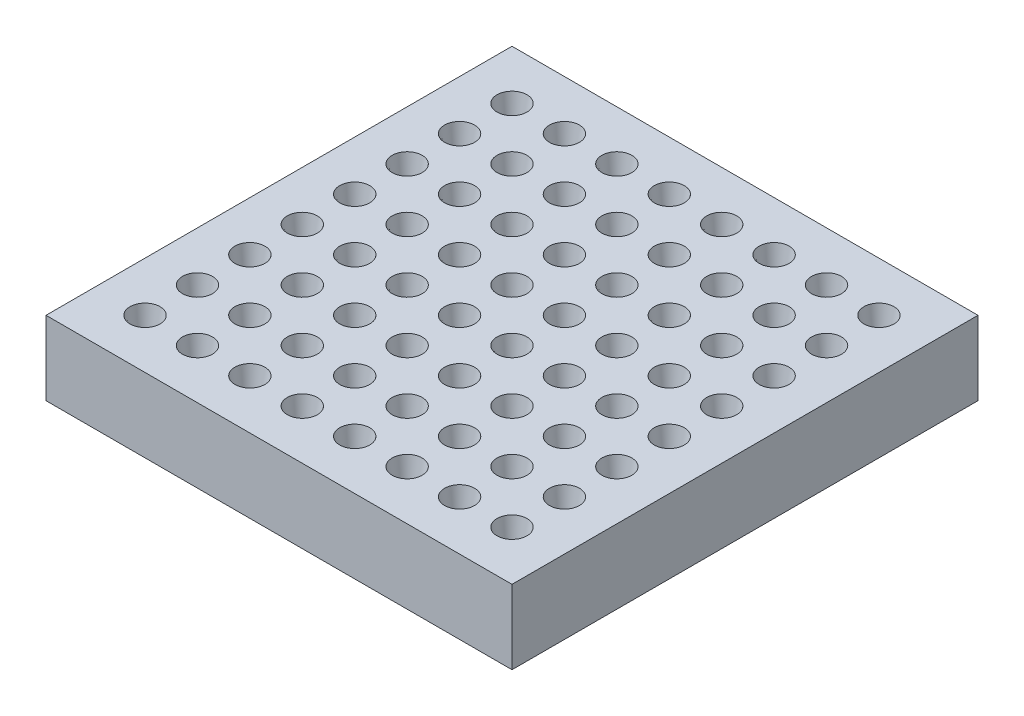
SolidWorks part; units mm, degrees
ref_plane "Front Plane" through (0, 0, 0) normal (0, 0, 1) x (1, 0, 0)
ref_plane "Top Plane" through (0, 0, 0) normal (0, 1, 0) x (1, 0, 0)
ref_plane "Right Plane" through (0, 0, 0) normal (1, 0, 0) x (0, 0, -1)
sketch "Sketch1" plane through (0, 0, 0) normal (0, 1, 0) x (1, 0, 0)
  line L1 (0, 0) -> (80, 0)
  line L2 (0, 0) -> (0, 80)
  line L3 (0, 80) -> (80, 80)
  line L4 (80, 0) -> (80, 80)
  dimension "D1" = 80
  dimension "D2" = 80
extrude "Boss-Extrude1" add sketch "Sketch1" along normal blind 12.7
sketch "Sketch4" plane through (0, 12.7, 0) normal (0, 1, 0) x (1, 0, 0)
  line L0 (80, 80) -> (0, 80) construction
  line L2 (0, 80) -> (0, 0) construction
  circle A0 centre (8.5, 71.5) radius 2.575
  dimension "D1" = 8.5
  dimension "D2" = 8.5
extrude "Cut-Extrude2" cut sketch "Sketch4" against normal blind 11.2 draft 8.75 contours A0
pattern_linear "LPattern1" count 8 spacing 9 along (1, 0, 0) count 8 spacing 9 along (0, 0, 1) of "Cut-Extrude2"
sketch "Sketch5" plane through (0, 0, -80) normal (0, 0, -1) x (-1, 0, 0)
  line L0 (-80, 0) -> (0, 0) construction
  line L1 (0, 12.7) -> (0, 0) construction
  circle A0 centre (-22.5, 0.95) radius 1.5
  dimension "D1" = 0.95
  dimension "D2" = 22.5
extrude "Cut-Extrude3" cut sketch "Sketch5" against normal blind 24
sketch "Sketch6" plane through (0, 0, -80) normal (0, 0, -1) x (-1, 0, 0)
  line L0 (-80, 12.7) -> (-80, 0) construction
  line L1 (-80, 0) -> (-23.6608, 0) construction
  circle A0 centre (-40, 6) radius 1
  dimension "D2" = 6
  dimension "D1" = 40
extrude "Cut-Extrude4" cut sketch "Sketch6" against normal blind 40
sketch "Sketch7" plane through (0, 12.7, 0) normal (0, 1, 0) x (1, 0, 0)
sketch "Sketch9" plane through (0, 1.5, 0) normal (0, 1, 0) x (1, 0, 0)
  line L0 (71.7267, 72.3204) -> (71.2733, 70.6796)
  circle A0 centre (71.5, 71.5) radius 0.8512 construction
  dimension "D1" = 1.6408
